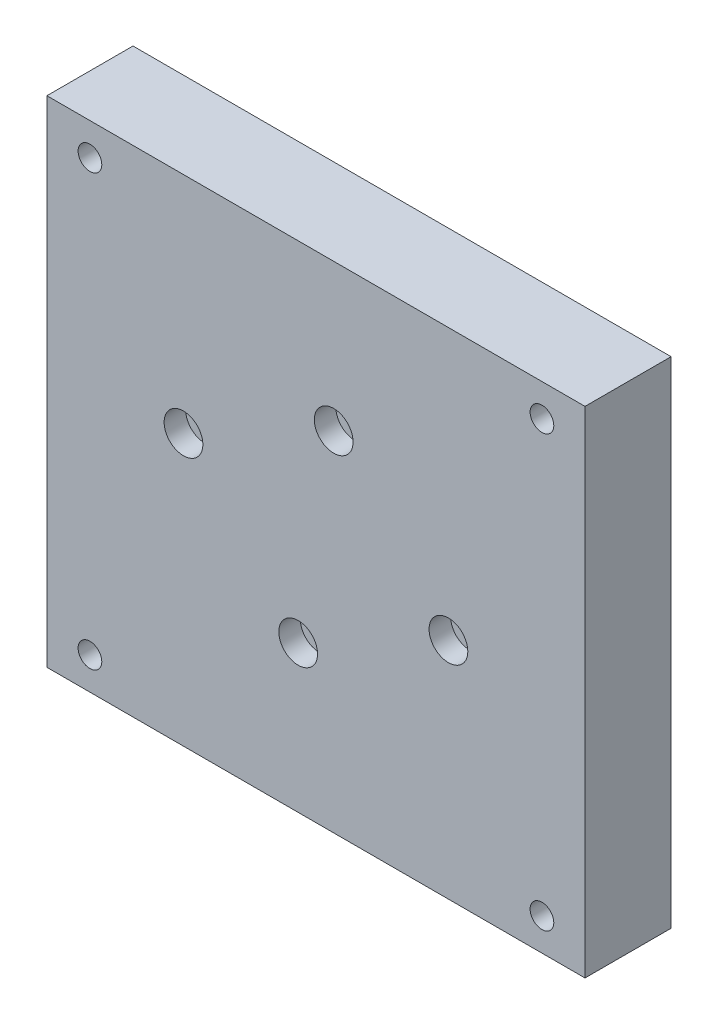
SolidWorks part; units mm, degrees
ref_plane "Front" through (0, 0, 0) normal (0, 0, 1) x (1, 0, 0)
ref_plane "Top" through (0, 0, 0) normal (0, 1, 0) x (1, 0, 0)
ref_plane "Right" through (0, 0, 0) normal (1, 0, 0) x (0, 0, -1)
sketch "草图1" plane through (0, 0, 0) normal (0, 0, 1) x (1, 0, 0)
  line L1 (25, -23) -> (-25, -23)
  line L2 (25, -23) -> (25, 23)
  line L3 (25, 23) -> (-25, 23)
  line L4 (-25, -23) -> (-25, 23)
  line L5 (25, -23) -> (-25, 23) construction
  line L6 (25, 23) -> (-25, -23) construction
  point P0 (0, 0)
  point P6 (-25, 0)
  dimension "D1" = 50
  dimension "D2" = 46
extrude "凸台-拉伸1" add sketch "草图1" along normal blind 8 contours L1 L4 L3 L2
sketch "草图2" plane through (0, 0, 8) normal (0, 0, 1) x (1, 0, 0)
  circle A0 centre (-1.6497, -9.3557) radius 1.025 construction
  circle A1 centre (12.3101, -2.1706) radius 1.025 construction
  circle A2 centre (1.6497, 9.3557) radius 1.025 construction
  circle A3 centre (-12.3101, 2.1706) radius 1.025 construction
  circle A4 centre (-1.6497, -9.3557) radius 1.025
  circle A5 centre (12.3101, -2.1706) radius 1.025
  circle A6 centre (1.6497, 9.3557) radius 1.025
  circle A7 centre (-12.3101, 2.1706) radius 1.025
extrude "切除-拉伸1" cut sketch "草图2" against normal blind 5
sketch "草图3" plane through (0, 0, 8) normal (0, 0, 1) x (1, 0, 0)
  circle A0 centre (-12.3101, 2.1706) radius 1.8
  circle A1 centre (1.6497, 9.3557) radius 1.8
  circle A2 centre (12.3101, -2.1706) radius 1.8
  circle A3 centre (-1.6497, -9.3557) radius 1.8
  dimension "D1" = 3.6
extrude "切除-拉伸2" cut sketch "草图3" against normal blind 2
sketch "草图4" plane through (0, 0, 0) normal (0, 0, -1) x (-1, 0, 0)
  line L0 (-25, -23) -> (25, -23) construction
  line L1 (25, -23) -> (25, 23) construction
  circle A0 centre (21, -20) radius 1.1
  circle A1 centre (-21, -20) radius 1.1
  dimension "D1" = 2.2
  dimension "D2" = 42
  dimension "D3" = 3
  dimension "D4" = 3
  dimension "D5" = 4
extrude "切除-拉伸3" cut sketch "草图4" against normal blind 24
ref_plane "基准面1" through (0, 0, 0) normal (0, -1, 0) x (-1, 0, 0)
mirror "镜向1" about plane through (0, 0, 0) normal (0, -1, 0) of "切除-拉伸3"
